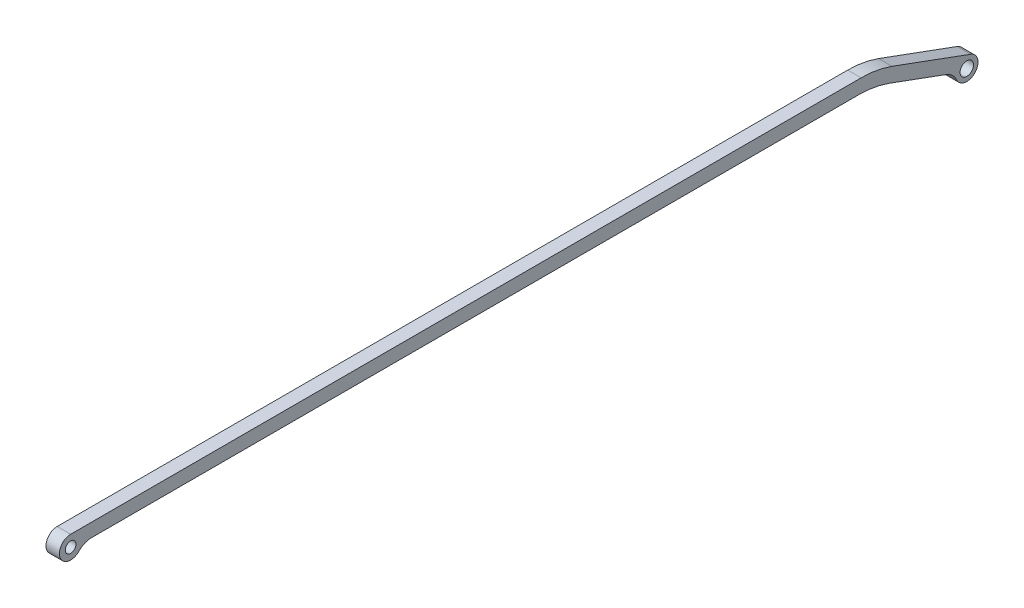
SolidWorks part; units mm, degrees
ref_plane "Piano frontale" through (0, 0, 0) normal (0, 0, 1) x (1, 0, 0)
ref_plane "Piano superiore" through (0, 0, 0) normal (0, 1, 0) x (1, 0, 0)
ref_plane "Piano destro" through (0, 0, 0) normal (1, 0, 0) x (0, 0, -1)
sketch "Schizzo2" plane through (0, 0, 0) normal (1, 0, 0) x (0, 0, -1)
  line L0 (-8.3323, 0.3882) -> (0.4305, -2.8265)
  line L1 (-99.9297, 1) -> (-11.7764, 1)
  line L2 (0, 55) -> (0, -55) construction
  line L3 (-97.5845, -0.5) -> (-12.0428, -0.5)
  line L5 (-2.2878, -3.427) -> (-8.5987, -1.1118)
  arc A0 (-99.9297, 1) -> (-99.0277, -1.1154) centre (-99.9297, -0.25) ccw
  circle A1 centre (-99.9297, -0.25) radius 0.6
  arc A2 (-99.0277, -1.1154) -> (-97.5845, -0.5) centre (-97.5845, -2.5) cw
  arc A3 (-1.1449, -4.5018) -> (0.4305, -2.8265) centre (0, -4) ccw
  circle A4 centre (0, -4) radius 0.75
  arc A5 (-1.1449, -4.5018) -> (-2.2878, -3.427) centre (-2.9766, -5.3046) ccw
  arc A6 (-8.3323, 0.3882) -> (-11.7764, 1) centre (-11.7764, -9) ccw
  arc A7 (-8.5987, -1.1118) -> (-12.0428, -0.5) centre (-12.0428, -10.5) ccw
  point P19 (-10, 1)
  dimension "D5" = 2.5
  dimension "D6" = 1.2
  dimension "D2" = 2
  dimension "D9" = 2.5
  dimension "D10" = 1.5
  dimension "D7" = 2
  dimension "D13" = 10
  dimension "D1" = 1.5
  dimension "D3" = 5
  dimension "D4" = 1
  dimension "D8" = 10
  dimension "D11" = 100
  dimension "D12" = 1.5
extrude "Estrusione-Estrusione1" add sketch "Schizzo2" along normal blind 1.5
